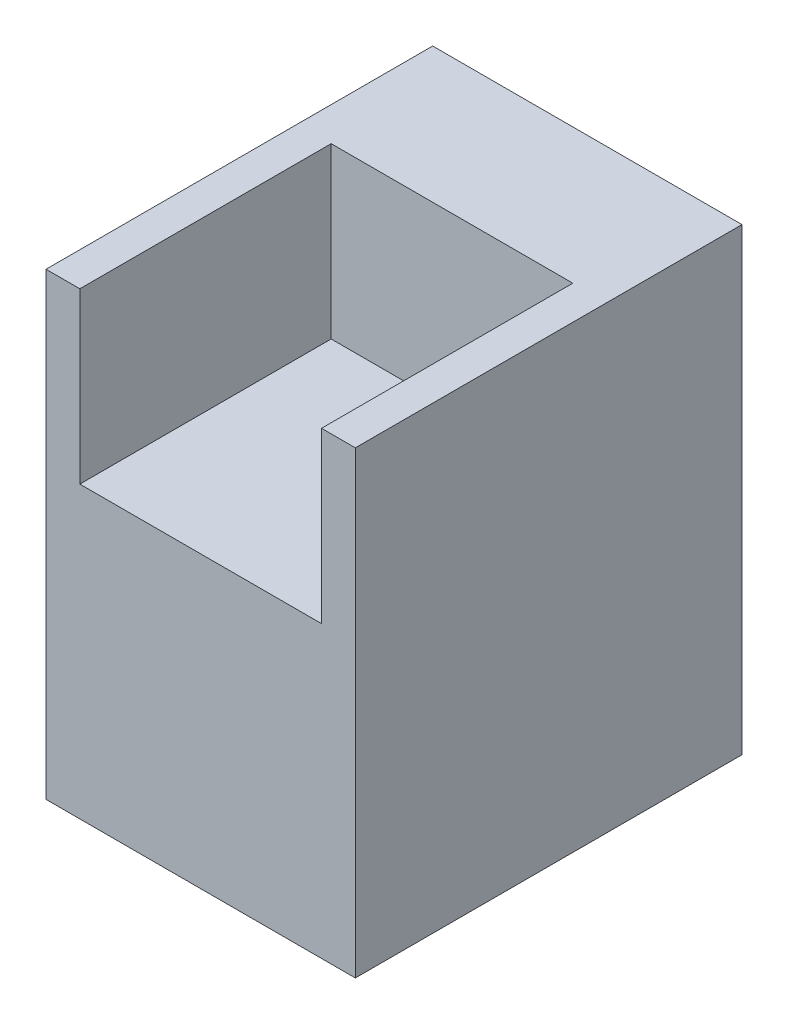
SolidWorks part; units mm, degrees
ref_plane "Front Plane" through (0, 0, 0) normal (0, 0, 1) x (1, 0, 0)
ref_plane "Top Plane" through (0, 0, 0) normal (0, 1, 0) x (1, 0, 0)
ref_plane "Right Plane" through (0, 0, 0) normal (1, 0, 0) x (0, 0, -1)
other "Configuration Table"
sketch "Sketch1" plane through (0, 0, 0) normal (0, 0, 1) x (1, 0, 0)
  line L1 (30, 120) -> (670, 120)
  line L2 (30, 120) -> (30, 1070)
  line L3 (30, 1070) -> (670, 1070)
  line L4 (670, 120) -> (670, 1070)
extrude "PRESS_PZP400_govde_SATIN_ALINAN_1" add sketch "Sketch1" against normal blind 800 separate body
sketch "Sketch2" plane through (0, 0, 0) normal (0, 0, 1) x (1, 0, 0)
  line L1 (100, 720) -> (600, 720)
  line L2 (100, 720) -> (100, 1080)
  line L3 (100, 1080) -> (600, 1080)
  line L4 (600, 720) -> (600, 1080)
extrude "PRESS_PZP400_govde_SATIN_ALINAN_2" cut sketch "Sketch2" against normal blind 521 from offset 1
